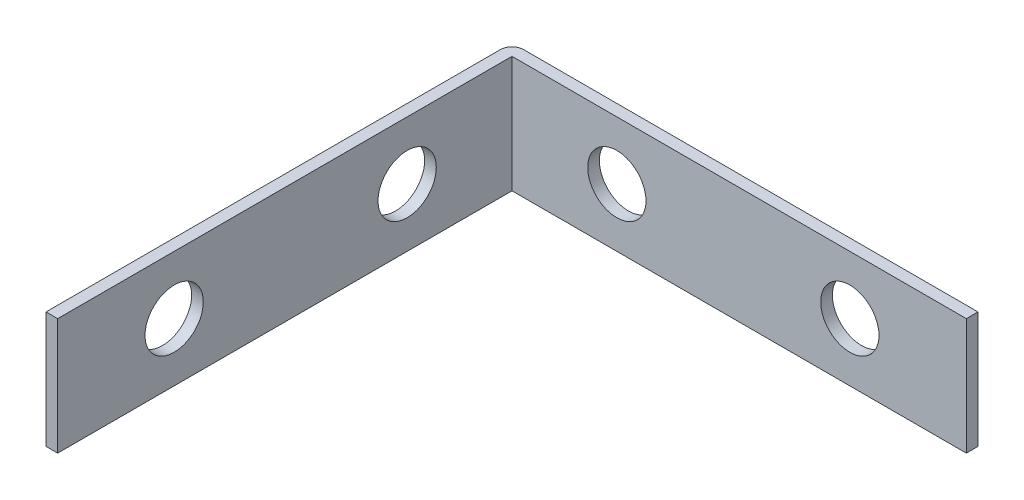
SolidWorks part; units mm, degrees
ref_plane "Alzado" through (0, 0, 0) normal (0, 0, 1) x (1, 0, 0)
ref_plane "Planta" through (0, 0, 0) normal (0, 1, 0) x (1, 0, 0)
ref_plane "Vista lateral" through (0, 0, 0) normal (1, 0, 0) x (0, 0, -1)
sketch "Croquis1" plane through (0, 0, 0) normal (0, 1, 0) x (1, 0, 0)
  line L0 (-24.4468, -22.2407) -> (-24.4468, 16.7593)
  line L1 (14.5532, 17.7593) -> (-24.4468, 17.7593)
  line L2 (-25.4468, 16.7593) -> (-25.4468, -22.2407)
  line L3 (-25.4468, -22.2407) -> (-24.4468, -22.2407)
  line L4 (-24.4468, 16.7593) -> (14.5532, 16.7593)
  line L5 (-25.4468, -22.2407) -> (-25.631, -22.1546)
  line L8 (14.5532, 16.7593) -> (14.5532, 17.7593)
  arc A0 (-25.4468, 16.7593) -> (-24.4468, 17.7593) centre (-24.4468, 16.7593) cw
  point P9 (-25.4468, 17.7593)
  dimension "D2" = 1
  dimension "D1" = 1
  dimension "D3" = 40
  dimension "D4" = 40
extrude "Saliente-Extruir1" add sketch "Croquis1" along normal blind 10 contours A0 L2 L3 L0 L4 L8 L1
sketch "Croquis2" plane through (0, 0, -16.7593) normal (0, 0, 1) x (1, 0, 0)
  line L0 (-25.4468, 10) -> (-25.4468, 0) construction
  line L1 (-24.4468, 10) -> (14.5532, 10) construction
  circle A0 centre (4.5532, 5) radius 2.5
  circle A1 centre (-15.4468, 5) radius 2.5
  dimension "D1" = 30
  dimension "D2" = 10
  dimension "D3" = 5
  dimension "D4" = 5
extrude "Cortar-Extruir1" cut sketch "Croquis2" against normal up to surface (1 mm away) up to face at (-4.9468, 5, -17.7593)
sketch "Croquis3" plane through (-24.4468, 0, 0) normal (1, 0, 0) x (0, 0, -1)
  line L0 (17.7593, 10) -> (17.7593, 0) construction
  line L1 (-22.2407, 10) -> (16.7593, 10) construction
  circle A0 centre (-12.2407, 5) radius 2.5
  circle A1 centre (7.7593, 5) radius 2.5
  dimension "D1" = 10
  dimension "D2" = 30
  dimension "D3" = 5
  dimension "D4" = 5
extrude "Cortar-Extruir2" cut sketch "Croquis3" against normal up to surface (1 mm away) up to face at (-25.4468, 5, 2.7407)
